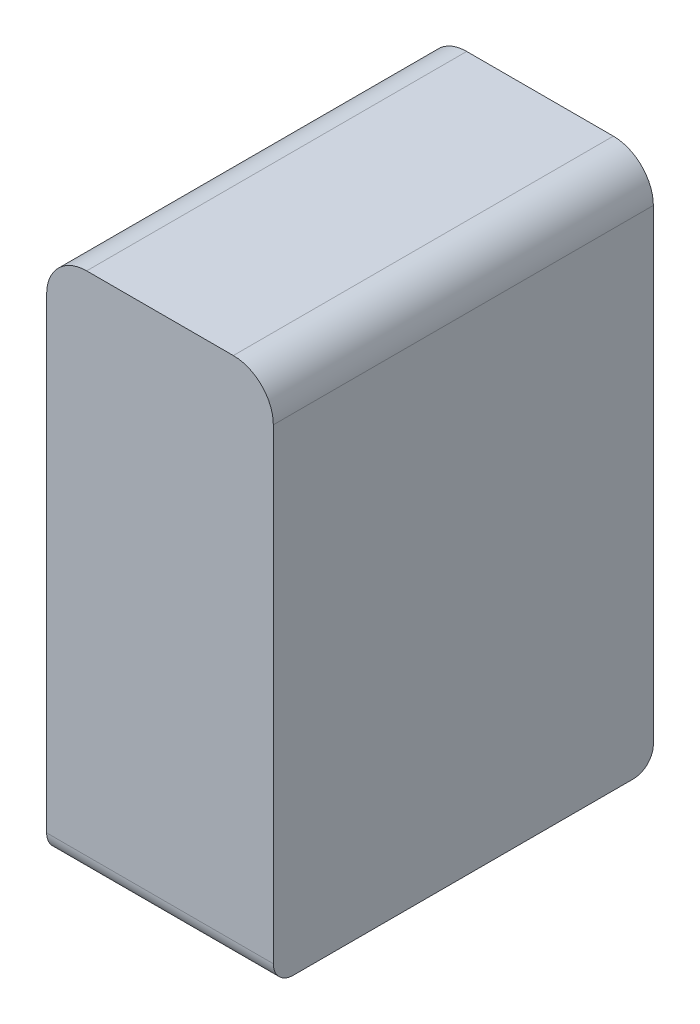
SolidWorks part; units mm, degrees
ref_plane "Front" through (0, 0, 0) normal (0, 0, 1) x (1, 0, 0)
ref_plane "Top" through (0, 0, 0) normal (0, 1, 0) x (1, 0, 0)
ref_plane "Right" through (0, 0, 0) normal (1, 0, 0) x (0, 0, -1)
sketch "Sketch1" plane through (0, 0, 0) normal (0, 0, 1) x (1, 0, 0)
  line L1 (-17, -39.5) -> (17, -39.5)
  line L2 (-17, -39.5) -> (-17, 39.5)
  line L3 (-17, 39.5) -> (17, 39.5)
  line L4 (17, -39.5) -> (17, 39.5)
  line L5 (-17, -39.5) -> (17, 39.5) construction
  line L6 (-17, 39.5) -> (17, -39.5) construction
  point P0 (0, 0)
  dimension "D1" = 79
  dimension "D2" = 34
extrude "Boss-Extrude1" add sketch "Sketch1" along normal blind 57
fillet "Fillet1" radius 6 2 edges at (17, 39.5, 28.5) (-17, 39.5, 28.5)
fillet "Fillet2" radius 3 2 edges at (0, -39.5, 57) (0, -39.5, 0)
